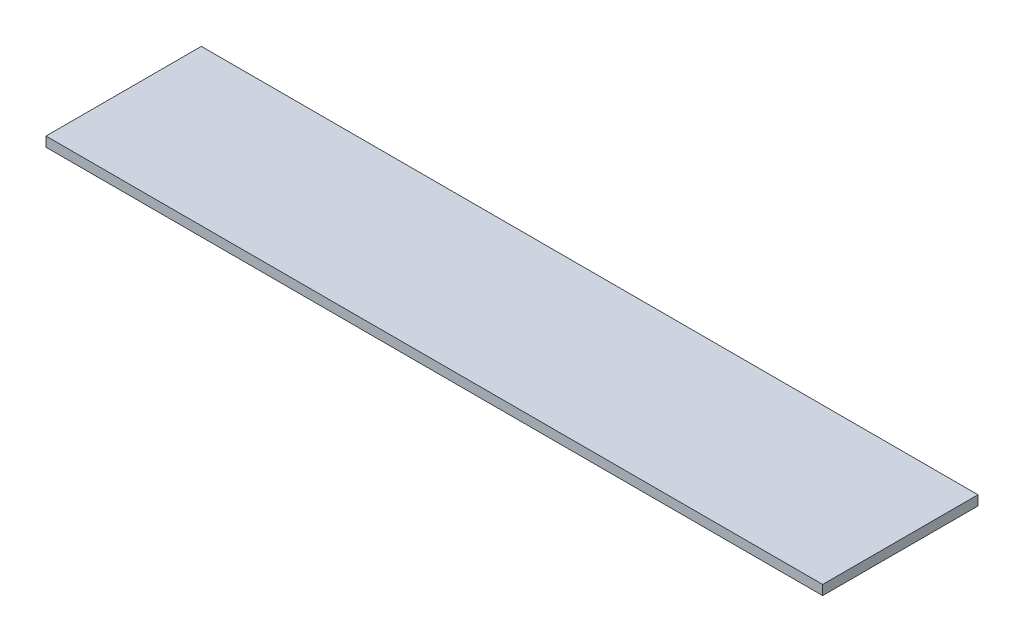
SolidWorks part; units mm, degrees
ref_plane "前视基准面" through (0, 0, 0) normal (0, 0, 1) x (1, 0, 0)
ref_plane "上视基准面" through (0, 0, 0) normal (0, 1, 0) x (1, 0, 0)
ref_plane "右视基准面" through (0, 0, 0) normal (1, 0, 0) x (0, 0, -1)
other "Configuration Table"
sketch "草图1" plane through (0, 0, 0) normal (0, 1, 0) x (1, 0, 0)
  line L0 (0, -4) -> (40, -4)
  line L1 (0, 0) -> (40, 0) construction
  line L2 (0, -4) -> (0, 4)
  line L3 (0, 4) -> (40, 4)
  line L4 (40, -4) -> (40, 4)
  dimension "D1" = 4
  dimension "D2" = 40
extrude "凸台-拉伸1" add sketch "草图1" along normal blind 0.5
